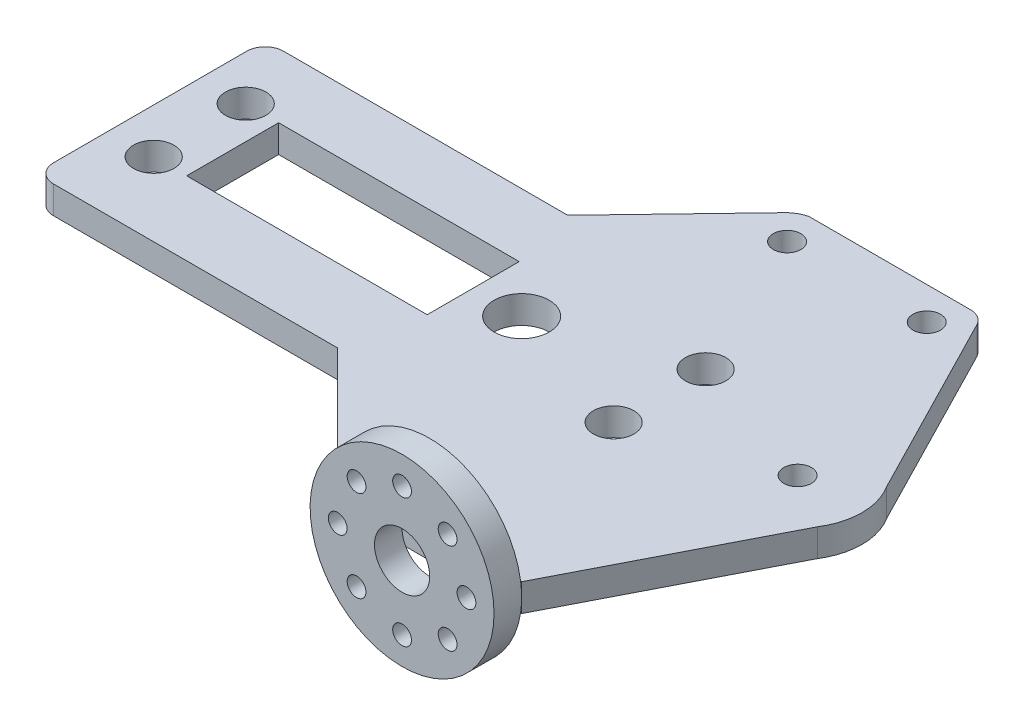
SolidWorks part; units mm, degrees
ref_plane "正面" through (0, 0, 0) normal (0, 0, 1) x (1, 0, 0)
ref_plane "平面" through (0, 0, 0) normal (0, 1, 0) x (1, 0, 0)
ref_plane "右側面" through (0, 0, 0) normal (1, 0, 0) x (0, 0, -1)
sketch "ｽｹｯﾁ1" plane through (0, 0, 0) normal (0, 0, 1) x (1, 0, 0)
  circle A1 centre (-25.029, 61.0503) radius 1.02
  circle A2 centre (-29.9787, 59) radius 1.02
  circle A3 centre (-34.9285, 61.0503) radius 1.02
  circle A4 centre (-36.9787, 66) radius 1.02
  circle A5 centre (-34.9285, 70.9497) radius 1.02
  circle A6 centre (-29.9787, 73) radius 1.02
  circle A7 centre (-25.029, 70.9497) radius 1.02
  circle A8 centre (-22.9787, 66) radius 1.02
  circle A9 centre (-29.9787, 66) radius 10
  circle A11 centre (-29.9787, 66) radius 1.5
  point P23 (-29.9787, 66)
  dimension "D1" = 8
extrude "ﾎﾞｽ - 押し出し1" add sketch "ｽｹｯﾁ1" along normal blind 3
sketch "ｽｹｯﾁ2" plane through (0, 0, 3) normal (0, 0, 1) x (1, 0, 0)
  circle A1 centre (-29.9787, 66) radius 5
extrude "ﾎﾞｽ - 押し出し2" add sketch "ｽｹｯﾁ2" along normal blind 1
sketch "ｽｹｯﾁ3" plane through (0, 0, 3) normal (0, 0, -1) x (-1, 0, 0)
  circle A0 centre (29.9787, 66) radius 3
extrude "ｶｯﾄ - 押し出し1" cut sketch "ｽｹｯﾁ3" against normal blind 0.5 and the other way blind 10
sketch "ｽｹｯﾁ4" plane through (0, 0, 3.5) normal (0, 0, -1) x (-1, 0, 0)
  circle A0 centre (29.9787, 66) radius 1.5
extrude "ｶｯﾄ - 押し出し2" cut sketch "ｽｹｯﾁ4" against normal blind 8.5
sketch "ｽｹｯﾁ5" plane through (0, 0, 0) normal (0, 0, -1) x (-1, 0, 0)
  circle A0 centre (29.9787, 66) radius 3
extrude "ｶｯﾄ - 押し出し3" cut sketch "ｽｹｯﾁ5" against normal blind 10
sketch "ｽｹｯﾁ6" plane through (0, 0, 0) normal (0, 0, -1) x (-1, 0, 0)
  line L5 (29.9787, 64.5) -> (89.9787, 64.5)
  line L6 (29.9787, 67.5) -> (89.9787, 67.5)
  line L7 (89.9787, 67.5) -> (89.9787, 64.5)
  line L8 (29.9787, 67.5) -> (7.9787, 67.5)
  line L9 (7.9787, 67.5) -> (7.9787, 64.5)
  line L10 (7.9787, 64.5) -> (29.9787, 64.5)
extrude "ﾎﾞｽ - 押し出し3" add sketch "ｽｹｯﾁ6" along normal blind 50
sketch "ｽｹｯﾁ7" plane through (0, 67.5, 0) normal (0, 1, 0) x (1, 0, 0)
  line L0 (-39.9855, 0) -> (-51.974, 12)
  line L2 (-11, 0) -> (11, 0) construction
  line L4 (-38.7637, 50) -> (-21.1937, 50)
  line L5 (-19.9719, 0) -> (-9.0742, 21.2401)
  line L6 (-19.4142, 48.913) -> (-9.0742, 28.7599)
  line L7 (-38.7637, 50) -> (-38.4407, 54.8736)
  line L13 (-76.3971, 30) -> (-50.2469, 30)
  line L14 (-76.3971, 30) -> (-76.3971, 20)
  line L18 (-84.8643, 14) -> (-84.8643, 35)
  line L20 (-76.3971, 20) -> (-50.2469, 20)
  line L21 (-50.2469, 30) -> (-50.2469, 20)
  line L25 (-38.4407, 54.8736) -> (-103.0445, 56.7084)
  line L26 (-103.0445, 56.7084) -> (-100.1452, -3.5118)
  line L27 (-100.1452, -3.5118) -> (-39.9855, 0)
  line L28 (-21.1937, 50) -> (-19.9719, 56.2001)
  line L29 (-19.9719, 56.2001) -> (11.1424, 56.2001)
  line L30 (11.1424, 56.2001) -> (8.8608, -5.1086)
  line L31 (8.8608, -5.1086) -> (-19.9719, 0)
  line L32 (-51.974, 37) -> (-40.5432, 48.913)
  line L33 (-82.8643, 37) -> (-51.974, 37)
  line L34 (-82.8643, 12) -> (-51.974, 12)
  circle A0 centre (-14.9787, 25) radius 1.5
  arc A3 (-9.0742, 28.7599) -> (-9.0742, 21.2401) centre (-14.9787, 25) cw
  arc A4 (-21.1937, 50) -> (-19.4142, 48.913) centre (-21.1937, 48) cw
  circle A6 centre (-22.3872, 46.4446) radius 1.5
  circle A7 centre (-37.5702, 46.4446) radius 1.5
  circle A8 centre (-44.9787, 25) radius 3
  circle A9 centre (-79.9787, 30) radius 2.2
  circle A10 centre (-79.9787, 20) radius 2.2
  circle A11 centre (-29.9787, 30) radius 2.2
  circle A12 centre (-29.9787, 20) radius 2.2
  arc A14 (-84.8643, 14) -> (-82.8643, 12) centre (-82.8643, 14) ccw
  arc A15 (-84.8643, 35) -> (-82.8643, 37) centre (-82.8643, 35) cw
  arc A18 (-38.7637, 50) -> (-40.5432, 48.913) centre (-37.8688, 46.5349) ccw
  point P3 (0, 0)
  point P7 (0, 0)
  point P17 (-19.9719, 50)
  point P19 (0, 0)
  point P41 (-39.9855, 50)
extrude "ｶｯﾄ - 押し出し8" cut sketch "ｽｹｯﾁ7" against normal blind 50 contours A18 L14 L18 L0 L34 A14 A15 L33 L32 | L26 L27 L0 L18 L14 L7 L25 | L21 L13 L14 L20 | A8 | A7 | A11 | A12 | A0 | L31 L30 L29 L28 L14 L13 L7 | L14 A4 L6 A3 L13 | L13 A3 L5 L7 | A9 | A10 | A6
sketch "ｽｹｯﾁ9" plane through (0, 0, 0) normal (1, 0, 0) x (0, 0, -1)
  line L0 (-3, 76) -> (-3, 56) construction
  line L1 (-6.7657, 72.9402) -> (-3, 72.9402)
  line L2 (-6.7657, 72.9402) -> (-6.7657, 61)
  line L3 (-6.7657, 61) -> (-3, 61)
  line L4 (-3, 72.9402) -> (-3, 61)
  line L5 (-3, 71) -> (-3, 61) construction
extrude "ｶｯﾄ - 押し出し9" cut sketch "ｽｹｯﾁ9" against normal blind 50
